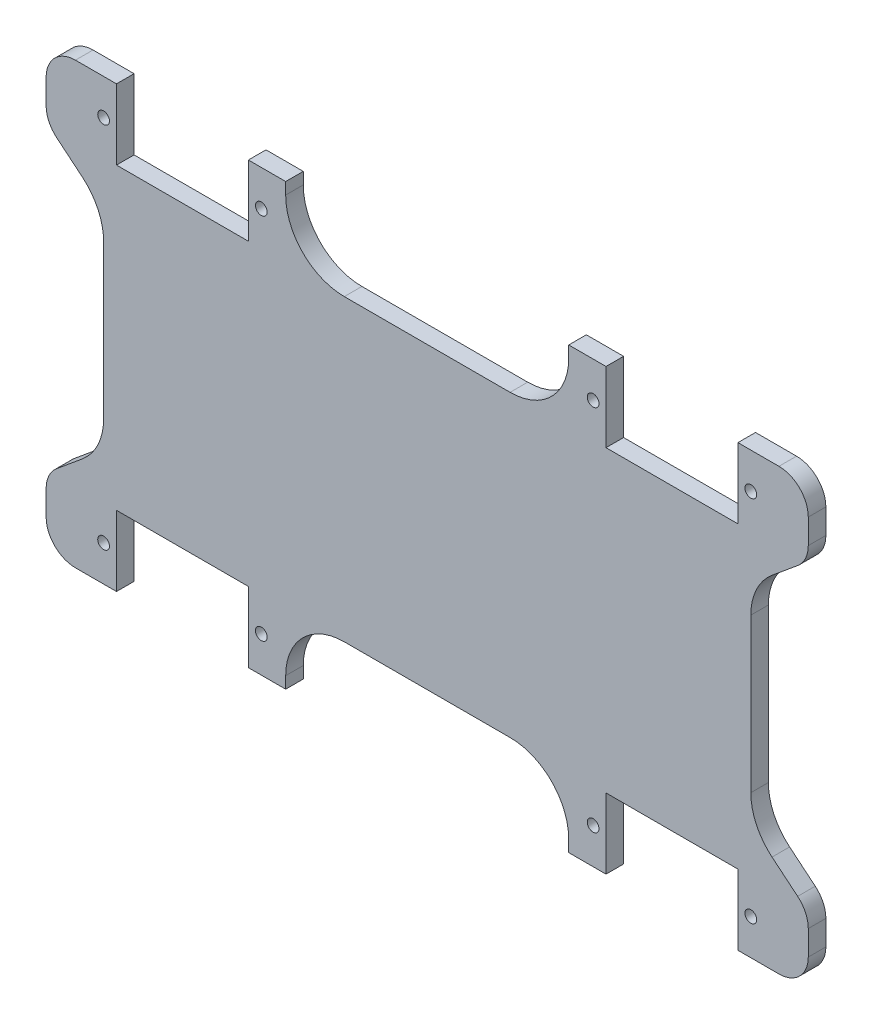
SolidWorks part; units mm, degrees
ref_plane "Front Plane" through (0, 0, 0) normal (0, 0, 1) x (1, 0, 0)
ref_plane "Top Plane" through (0, 0, 0) normal (0, 1, 0) x (1, 0, 0)
ref_plane "Right Plane" through (0, 0, 0) normal (1, 0, 0) x (0, 0, -1)
sketch "Sketch1" plane through (0, 0, 0) normal (0, 0, 1) x (1, 0, 0)
  line L0 (0, 0) -> (60.7869, 0) construction
  line L1 (65, -37.5) -> (-65, -37.5) construction
  line L2 (65, -37.5) -> (65, 37.5) construction
  line L3 (65, 37.5) -> (-65, 37.5) construction
  line L4 (-65, -37.5) -> (-65, 37.5) construction
  line L5 (65, -37.5) -> (-65, 37.5) construction
  line L6 (65, 37.5) -> (-65, -37.5) construction
  line L7 (0, 0) -> (0, 49.3998) construction
  line L8 (30.5, 37.5) -> (30.5, 25.5)
  line L9 (30.5, 25.5) -> (53, 25.5)
  line L10 (53, 25.5) -> (53, 37.5)
  line L11 (41.75, 25.5) -> (41.75, 34.55) construction
  line L12 (53, 37.5) -> (60, 37.5)
  line L13 (65, 32.5) -> (65, 28.2834)
  line L14 (63.1897, 24.433) -> (58.8206, 20.8135)
  line L15 (55.2, 13.1127) -> (55.2, -13.1127)
  line L16 (30.5, 37.5) -> (24.142, 37.5)
  line L17 (24.142, 37.5) -> (24.142, 35.5)
  line L18 (14.142, 25.5) -> (-14.142, 25.5)
  line L19 (-55.2, 13.1127) -> (-55.2, -13.1127)
  line L20 (-63.1897, 24.433) -> (-58.8206, 20.8135)
  line L21 (-65, 32.5) -> (-65, 28.2834)
  line L22 (-53, 37.5) -> (-60, 37.5)
  line L23 (-53, 25.5) -> (-53, 37.5)
  line L24 (-30.5, 25.5) -> (-53, 25.5)
  line L25 (-30.5, 37.5) -> (-30.5, 25.5)
  line L26 (-24.142, 37.5) -> (-24.142, 35.5)
  line L27 (-30.5, 37.5) -> (-24.142, 37.5)
  line L28 (-30.5, -37.5) -> (-24.142, -37.5)
  line L29 (-24.142, -37.5) -> (-24.142, -35.5)
  line L30 (-30.5, -37.5) -> (-30.5, -25.5)
  line L31 (-30.5, -25.5) -> (-53, -25.5)
  line L32 (-53, -25.5) -> (-53, -37.5)
  line L33 (-53, -37.5) -> (-60, -37.5)
  line L34 (-65, -32.5) -> (-65, -28.2834)
  line L35 (-63.1897, -24.433) -> (-58.8206, -20.8135)
  line L36 (14.142, -25.5) -> (-14.142, -25.5)
  line L37 (24.142, -37.5) -> (24.142, -35.5)
  line L38 (30.5, -37.5) -> (24.142, -37.5)
  line L39 (63.1897, -24.433) -> (58.8206, -20.8135)
  line L40 (65, -32.5) -> (65, -28.2834)
  line L41 (53, -37.5) -> (60, -37.5)
  line L42 (53, -25.5) -> (53, -37.5)
  line L43 (30.5, -25.5) -> (53, -25.5)
  line L44 (30.5, -37.5) -> (30.5, -25.5)
  circle A0 centre (55.2, 31.4) radius 1
  circle A1 centre (28.3, 31.4) radius 1
  arc A2 (65, 28.2834) -> (63.1897, 24.433) centre (60, 28.2834) cw
  arc A3 (60, 37.5) -> (65, 32.5) centre (60, 32.5) cw
  arc A4 (24.142, 35.5) -> (14.142, 25.5) centre (14.142, 35.5) cw
  arc A5 (58.8206, 20.8135) -> (55.2, 13.1127) centre (65.2, 13.1127) ccw
  arc A6 (-58.8206, 20.8135) -> (-55.2, 13.1127) centre (-65.2, 13.1127) cw
  arc A7 (-65, 28.2834) -> (-63.1897, 24.433) centre (-60, 28.2834) ccw
  arc A8 (-60, 37.5) -> (-65, 32.5) centre (-60, 32.5) ccw
  circle A9 centre (-28.3, 31.4) radius 1
  arc A10 (-24.142, 35.5) -> (-14.142, 25.5) centre (-14.142, 35.5) ccw
  arc A11 (-24.142, -35.5) -> (-14.142, -25.5) centre (-14.142, -35.5) cw
  circle A12 centre (-28.3, -31.4) radius 1
  arc A13 (-60, -37.5) -> (-65, -32.5) centre (-60, -32.5) cw
  arc A14 (-65, -28.2834) -> (-63.1897, -24.433) centre (-60, -28.2834) cw
  arc A15 (-58.8206, -20.8135) -> (-55.2, -13.1127) centre (-65.2, -13.1127) ccw
  arc A16 (58.8206, -20.8135) -> (55.2, -13.1127) centre (65.2, -13.1127) cw
  arc A17 (24.142, -35.5) -> (14.142, -25.5) centre (14.142, -35.5) ccw
  arc A18 (60, -37.5) -> (65, -32.5) centre (60, -32.5) ccw
  arc A19 (65, -28.2834) -> (63.1897, -24.433) centre (60, -28.2834) ccw
  circle A20 centre (28.3, -31.4) radius 1
  circle A21 centre (55.2, -31.4) radius 1
  circle A22 centre (-55.2, 31.4) radius 1
  circle A23 centre (-55.2, -31.4) radius 1
  point P0 (0, 0)
  point P11 (55.2, 31.4)
  point P14 (53, 31.5)
  point P29 (65, 25.9326)
  point P57 (0, 25.5)
  point P58 (55.2, 0)
  point P59 (-55.2, 0)
  dimension "D6" = 2
  dimension "D9" = 5
  dimension "D10" = 10
  dimension "D1" = 130
  dimension "D2" = 75
  dimension "D3" = 22.5
  dimension "D4" = 2.2
  dimension "D5" = 5.9
  dimension "D7" = 12
  dimension "D8" = 12
extrude "Boss-Extrude1" add sketch "Sketch1" along normal mid plane 3
ref_plane "Plane1" through (0, 0, 0) normal (0, 1, 0) x (1, 0, 0)
ref_plane "Plane2" through (0, 0, 0) normal (1, 0, 0) x (0, 0, -1)
